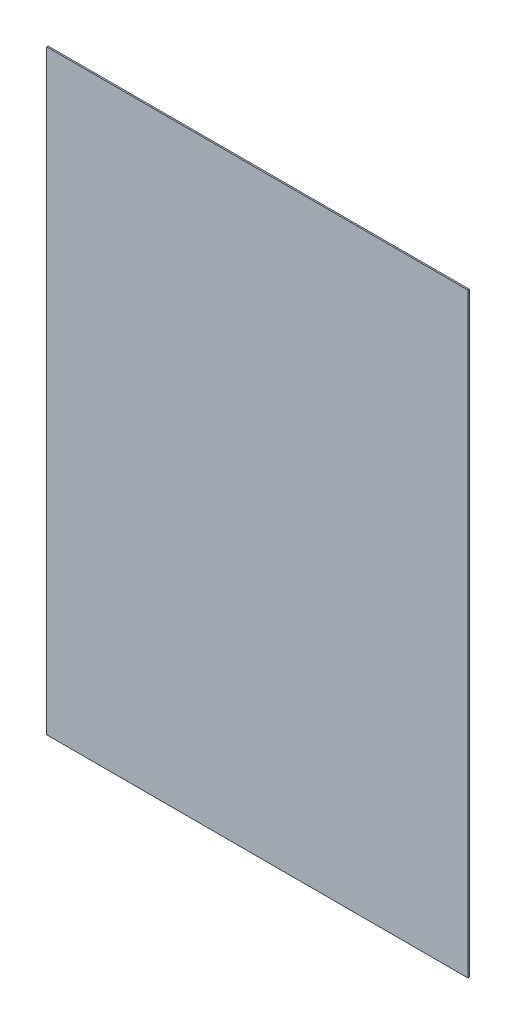
SolidWorks part; units mm, degrees
ref_plane "Alzado" through (0, 0, 0) normal (0, 0, 1) x (1, 0, 0)
ref_plane "Planta" through (0, 0, 0) normal (0, 1, 0) x (1, 0, 0)
ref_plane "Vista lateral" through (0, 0, 0) normal (1, 0, 0) x (0, 0, -1)
sketch "Croquis1" plane through (0, 0, 0) normal (0, 0, 1) x (1, 0, 0)
  line L1 (0, 0) -> (148.5, 0)
  line L2 (0, 0) -> (0, 210)
  line L3 (0, 210) -> (148.5, 210)
  line L4 (148.5, 0) -> (148.5, 210)
  dimension "D1" = 148.5
  dimension "D2" = 210
extrude "Saliente-Extruir1" add sketch "Croquis1" along normal blind 0.5
